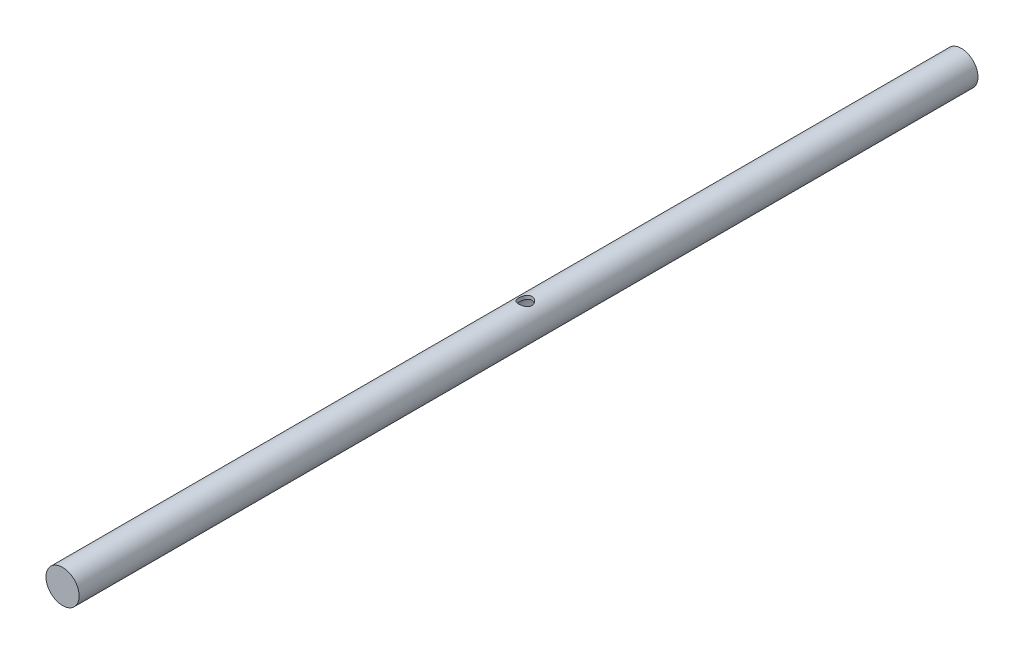
SolidWorks part; units mm, degrees
ref_plane "Front Plane" through (0, 0, 0) normal (0, 0, 1) x (1, 0, 0)
ref_plane "Top Plane" through (0, 0, 0) normal (0, 1, 0) x (1, 0, 0)
ref_plane "Right Plane" through (0, 0, 0) normal (1, 0, 0) x (0, 0, -1)
sketch "Sketch1" plane through (0, 0, 0) normal (0, 0, 1) x (1, 0, 0)
  circle A0 centre (0, 0) radius 3.175
  dimension "D1" = 6.35
extrude "Boss-Extrude1" add sketch "Sketch1" along normal blind 172.085
ref_plane "Plane1" through (0, 0, 86.0425) normal (0, 0, 1) x (1, 0, 0)
shell "Shell1" thickness 0.635
sketch "Sketch3" plane through (0, 0, 0) normal (0, 1, 0) x (1, 0, 0)
  line L1 (-3.4925, -86.0425) -> (3.4925, -86.0425) construction
  circle A0 centre (0, -83.5025) radius 1.27
  dimension "D1" = 2.54
  dimension "D2" = 2.54
extrude "Cut-Extrude3" cut sketch "Sketch3" along normal blind 5.08
